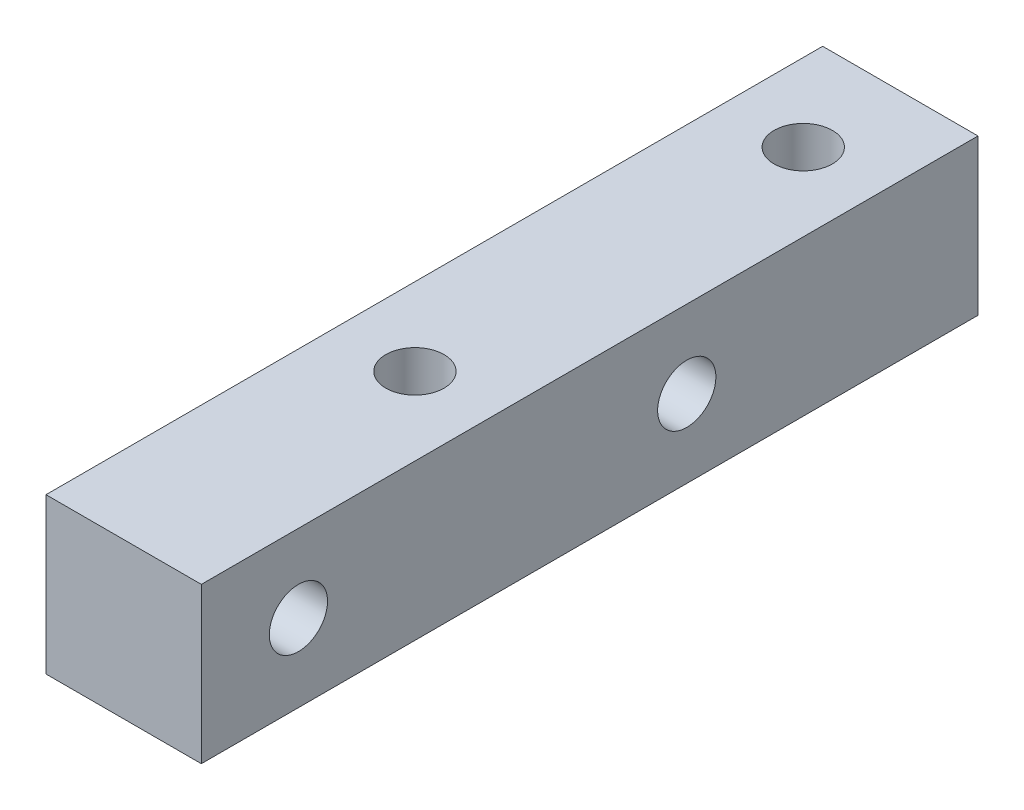
SolidWorks part; units mm, degrees
material "AISI 4130 钢，正火温度为 870C"
ref_plane "前视基准面" through (0, 0, 0) normal (0, 0, 1) x (1, 0, 0)
ref_plane "上视基准面" through (0, 0, 0) normal (0, 1, 0) x (1, 0, 0)
ref_plane "右视基准面" through (0, 0, 0) normal (1, 0, 0) x (0, 0, -1)
sketch "草图1" plane through (0, 0, 0) normal (0, 0, 1) x (1, 0, 0)
  line L1 (-4, 4) -> (4, 4)
  line L2 (-4, 4) -> (-4, -4)
  line L3 (-4, -4) -> (4, -4)
  line L4 (4, 4) -> (4, -4)
  line L5 (-4, 4) -> (4, -4) construction
  line L6 (-4, -4) -> (4, 4) construction
  point P0 (0, 0)
  dimension "D1" = 8
  dimension "D2" = 8
extrude "凸台-拉伸1" add sketch "草图1" along normal mid plane 40
sketch "草图2" plane through (4, 0, 0) normal (1, 0, 0) x (0, 0, -1)
  line L0 (-20, -4) -> (-20, 4) construction
  circle A0 centre (-15, 0) radius 1.5
  circle A1 centre (5, 0) radius 1.5
  dimension "D1" = 3
  dimension "D2" = 20
  dimension "D3" = 5
extrude "切除-拉伸1" cut sketch "草图2" against normal up to next
sketch "草图3" plane through (0, 4, 0) normal (0, 1, 0) x (1, 0, 0)
  line L0 (4, 20) -> (-4, 20) construction
  circle A0 centre (0, 15) radius 1.5
  circle A1 centre (0, -5) radius 1.5
  dimension "D1" = 20
  dimension "D2" = 5
  dimension "D3" = 3
extrude "切除-拉伸2" cut sketch "草图3" against normal up to next
